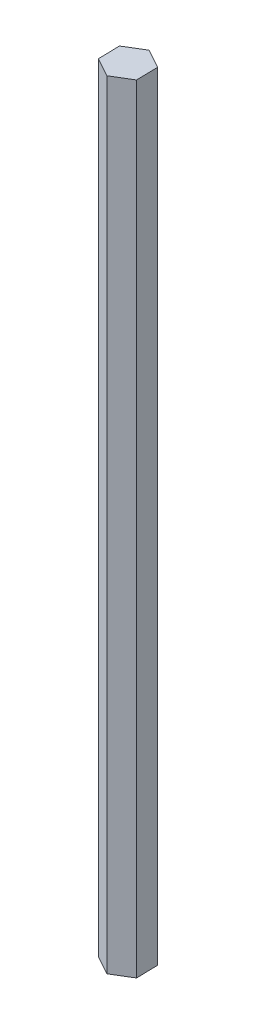
SolidWorks part; units mm, degrees
material "ABS"
ref_plane "Front Plane" through (0, 0, 0) normal (0, 0, 1) x (1, 0, 0)
ref_plane "Top Plane" through (0, 0, 0) normal (0, 1, 0) x (1, 0, 0)
ref_plane "Right Plane" through (0, 0, 0) normal (1, 0, 0) x (0, 0, -1)
sketch "Sketch1" plane through (0, 0, 0) normal (0, 1, 0) x (1, 0, 0)
  line L1 (2.0229, -1.1142) -> (1.9763, 1.1948)
  line L2 (1.9763, 1.1948) -> (-0.0465, 2.3089)
  line L3 (-0.0465, 2.3089) -> (-2.0229, 1.1142)
  line L4 (-2.0229, 1.1142) -> (-1.9763, -1.1948)
  line L5 (-1.9763, -1.1948) -> (0.0465, -2.3089)
  line L6 (0.0465, -2.3089) -> (2.0229, -1.1142)
  circle A0 centre (0, 0) radius 2 construction
  dimension "D1" = 4
extrude "Boss-Extrude1" add sketch "Sketch1" along normal blind 83
